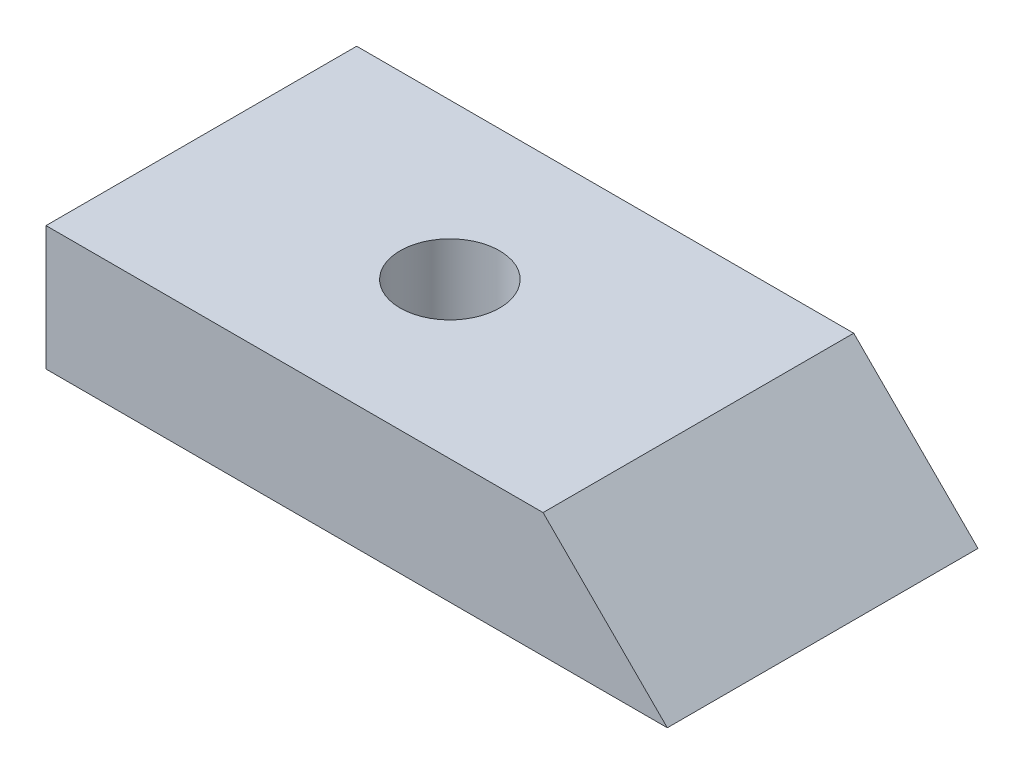
SolidWorks part; units mm, degrees
ref_plane "Front Plane" through (0, 0, 0) normal (0, 0, 1) x (1, 0, 0)
ref_plane "Top Plane" through (0, 0, 0) normal (0, 1, 0) x (1, 0, 0)
ref_plane "Right Plane" through (0, 0, 0) normal (1, 0, 0) x (0, 0, -1)
sketch "Sketch1" plane through (0, 0, 0) normal (0, 0, 1) x (1, 0, 0)
  line L0 (15, 0) -> (25, 0)
  line L1 (-25, 0) -> (15, 0)
  line L2 (-25, 0) -> (-25, 10)
  line L3 (-25, 10) -> (15, 10)
  line L4 (15, 0) -> (15, 10) construction
  line L5 (25, 0) -> (15, 10)
  point P0 (0, 0)
  dimension "D1" = 40
  dimension "D2" = 10
  dimension "D3" = 10
extrude "Boss-Extrude1" add sketch "Sketch1" along normal mid plane 25
sketch "Sketch2" plane through (0, 10, 0) normal (0, 1, 0) x (1, 0, 0)
  line L0 (41.3452, 0) -> (-41.3452, 0) construction
  line L1 (0, -34.7205) -> (0, 34.7205) construction
  line L2 (-25, -34.817) -> (-25, 34.817) construction
  circle A0 centre (-5, 0) radius 4
  point P4 (0, 0)
  point P8 (0, 0)
  point P13 (-25, 0)
  dimension "D2" = 8
  dimension "D1" = 20
extrude "Cut-Extrude1" cut sketch "Sketch2" against normal blind 25
